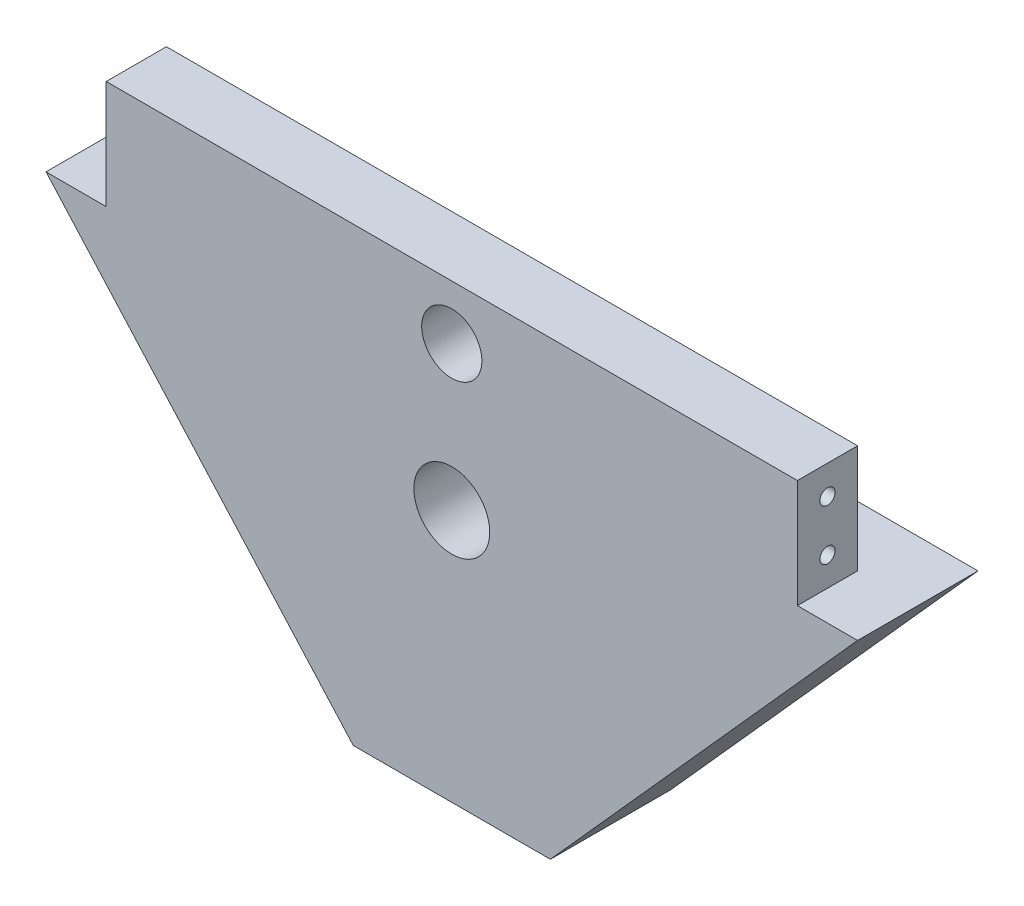
SolidWorks part; units mm, degrees
material "6061 Alloy"
ref_plane "Front Plane" through (0, 0, 0) normal (0, 0, 1) x (1, 0, 0)
ref_plane "Top Plane" through (0, 0, 0) normal (0, 1, 0) x (1, 0, 0)
ref_plane "Right Plane" through (0, 0, 0) normal (1, 0, 0) x (0, 0, -1)
other "Center of Mass"
sketch "Sketch1" plane through (0, 0, 0) normal (0, 0, 1) x (1, 0, 0)
  line L0 (-42.8001, -5.715) -> (-10.3954, -41.91)
  line L2 (-42.8001, -5.715) -> (-42.8001, 5.715)
  line L3 (-42.8001, 5.715) -> (42.8001, 5.715)
  line L4 (42.8001, -5.715) -> (42.8001, 5.715)
  line L5 (-10.3954, -41.91) -> (10.3954, -41.91)
  line L6 (10.3954, -41.91) -> (42.8001, -5.715)
  line L7 (0, 5.715) -> (0, -41.91) construction
  circle A0 centre (0, 0) radius 48.26 construction
  circle A1 centre (0, 0) radius 3.175 construction
  dimension "D1" = 96.52
  dimension "D2" = 6.35
  dimension "D6" = 6.35
  dimension "D3" = 2.54
  dimension "D4" = 5.08
  dimension "D5" = 5.08
  dimension "D7" = 5.08
extrude "Boss-Extrude1" add sketch "Sketch1" against normal blind 12.7
sketch "Sketch2" plane through (0, 0, 0) normal (0, 0, 1) x (1, 0, 0)
  circle A0 centre (0, 0) radius 3.175
  dimension "D1" = 6.35
extrude "Cut-Extrude1" cut sketch "Sketch2" against normal through all
sketch "Sketch3" plane through (42.8001, 0, 0) normal (1, 0, 0) x (0, 0, -1)
  line L0 (12.7, -5.715) -> (0, -5.715) construction
  line L1 (12.7, 5.715) -> (6.35, 5.715)
  line L2 (12.7, 5.715) -> (12.7, -5.715)
  line L3 (12.7, -5.715) -> (6.35, -5.715)
  line L4 (6.35, 5.715) -> (6.35, -5.715)
  line L5 (0, -5.715) -> (0, 5.715) construction
  dimension "D1" = 6.35
extrude "Cut-Extrude2" cut sketch "Sketch3" against normal through all
sketch "Sketch4" plane through (0, 0, 0) normal (0, 0, 1) x (1, 0, 0)
  line L0 (0, 0) -> (0, -15.24) construction
  circle A0 centre (0, -15.24) radius 4
  dimension "D2" = 8
  dimension "D1" = 15.24
extrude "Cut-Extrude3" cut sketch "Sketch4" against normal through all
sketch "Sketch5" plane through (0, 0, 0) normal (0, 0, 1) x (1, 0, 0)
  line L0 (39.6251, 3.175) -> (39.6251, -3.175) construction
  line L1 (42.8001, 5.715) -> (36.4501, 5.715) construction
  line L2 (42.8001, 5.715) -> (42.8001, -5.715) construction
  line L3 (42.8001, -5.715) -> (36.4501, -5.715) construction
  line L4 (36.4501, 5.715) -> (36.4501, -5.715) construction
  line L5 (36.4501, 0) -> (42.8001, 0) construction
  circle A0 centre (39.6251, 3.175) radius 1
  circle A1 centre (39.6251, -3.175) radius 1
  point P12 (39.6251, 0)
  dimension "D1" = 2
  dimension "D2" = 6.35
  dimension "D3" = 6.35
extrude "Cut-Extrude4" cut sketch "Sketch5" against normal through all
mirror "Mirror1" about plane through (0, 0, 0) normal (1, 0, 0) of "Cut-Extrude4"
sketch "Sketch6" plane through (0, 0, -6.35) normal (0, 0, -1) x (-1, 0, 0)
  line L0 (42.8001, -5.715) -> (-42.8001, -5.715) construction
  line L1 (-42.8001, 5.715) -> (-36.4501, 5.715)
  line L2 (-42.8001, 5.715) -> (-42.8001, -5.715)
  line L3 (-42.8001, -5.715) -> (-36.4501, -5.715)
  line L4 (-36.4501, 5.715) -> (-36.4501, -5.715)
  line L6 (42.8001, 5.715) -> (36.4501, 5.715)
  line L7 (42.8001, 5.715) -> (42.8001, -5.715)
  line L8 (42.8001, -5.715) -> (36.4501, -5.715)
  line L9 (36.4501, 5.715) -> (36.4501, -5.715)
  dimension "D1" = 6.35
extrude "Cut-Extrude5" cut sketch "Sketch6" against normal through all
sketch "Sketch7" plane through (-36.4501, 0, 0) normal (-1, 0, 0) x (0, 0, 1)
  line L0 (-3.175, 5.715) -> (-3.175, -5.715) construction
  line L1 (0, 5.715) -> (-6.35, 5.715) construction
  line L2 (0, -5.715) -> (-6.35, -5.715) construction
  point P0 (-3.175, 2.667)
  point P1 (-3.175, -2.667)
  point P8 (0, 0)
  point P10 (8.1518, 12.2987)
  point P11 (-4.2677, -5.715)
  dimension "D1" = 3.048
  dimension "D2" = 3.048
hole_wizard "M2x0.4 Tapped Hole1" positions "3DSketch1" profile "Sketch8" tap size "M2x0.4" standard "ANSI Metric"
sketch3d "3DSketch1"
  point P0 (-36.4501, 2.667, -3.175)
  point P3 (-36.4501, -2.667, -3.175)
sketch "Sketch8" plane through (-36.4501, 2.667, -3.175) normal (0, 1, 0) x (0, 0, 1)
  line L0 (0, 0) -> (0, 5.8147)
  line L1 (0, 5.8147) -> (0.8, 5.334)
  line L2 (0.8, 5.334) -> (0.8, 0)
  line L5 (0.8, 0) -> (0, 0)
  line L10 (0, 5.8147) -> (-0.8, 5.334) construction
  line L11 (0, -6.35) -> (0, 107.95) construction
  dimension "Tap Drill Dia." = 1.6
  dimension "Tap Drill Depth" = 5.334
  dimension "Drill Angle" = 118
cosmetic thread "Hole Thread1" parameters "D1"=4.064, "D2"=2
cosmetic thread "Hole Thread2" parameters "D1"=4.064, "D2"=2
ref_plane "Plane1" through (0, 0, 0) normal (1, 0, 0) x (0, 0, -1)
mirror "Mirror2" about plane through (0, 0, 0) normal (1, 0, 0) of "M2x0.4 Tapped Hole1"
cosmetic thread "Hole Thread3" parameters "D1"=4.064, "D2"=2
cosmetic thread "Hole Thread4" parameters "D1"=4.064, "D2"=2
